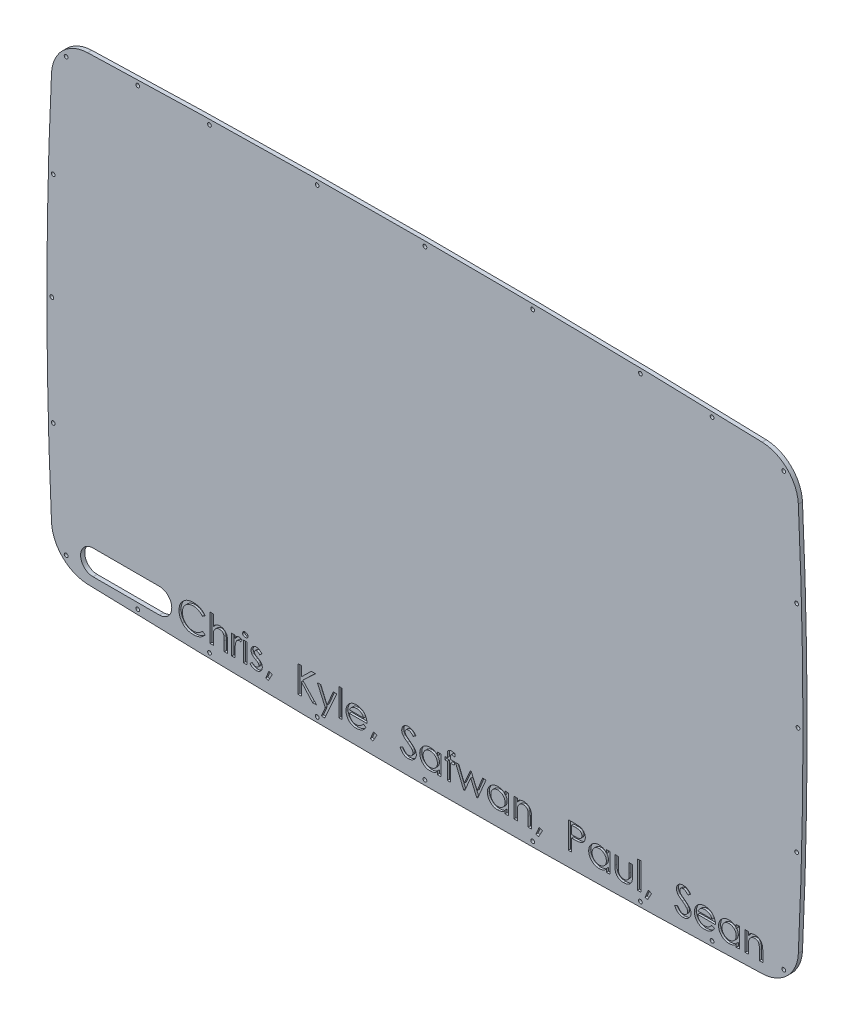
SolidWorks part; units mm, degrees
ref_plane "Front" through (0, 0, 0) normal (0, 0, 1) x (1, 0, 0)
ref_plane "Top" through (0, 0, 0) normal (0, 1, 0) x (1, 0, 0)
ref_plane "Right" through (0, 0, 0) normal (1, 0, 0) x (0, 0, -1)
sketch "Sketch1" plane through (0, 0, 0) normal (0, 0, 1) x (1, 0, 0)
  line L0 (79.622, -180.7786) -> (85.5592, -180.7149)
  line L1 (223.1034, -177.9577) -> (258.4236, -176.8528)
  circle A0 centre (-274.9542, -165.9116) radius 1.435
  arc A93 (-279.7814, -166.2105) -> (-275.1845, -170.7425) centre (-257.4604, -148.1676) ccw
  arc A94 (275.1845, -170.7425) -> (279.7814, -166.2105) centre (257.4604, -148.1676) ccw
  circle A100 centre (-274.9542, 164.9337) radius 1.4351
  circle A101 centre (-284.8103, 82.061) radius 1.4351
  circle A102 centre (-285.9024, 0) radius 1.4351
  circle A103 centre (-284.8103, -83.0389) radius 1.4351
  arc A104 (-258.4236, -176.8528) -> (-223.1034, -177.9577) centre (0, 7519.4009) ccw
  circle A105 centre (-220.0271, -174.2607) radius 1.4351
  circle A106 centre (-165.1, -175.6347) radius 1.4351
  arc A107 (-162.2131, -179.4816) -> (-85.5592, -180.7149) centre (0, 7519.4009) ccw
  arc A108 (-168.1492, -179.3542) -> (-162.2131, -179.4816) centre (0, 7519.4009) ccw
  circle A109 centre (-82.55, -176.963) radius 1.4351
  circle A110 centre (0, -177.4057) radius 1.4351
  circle A111 centre (82.55, -176.963) radius 1.4351
  circle A112 centre (165.1, -175.6347) radius 1.4351
  circle A113 centre (220.0271, -174.2607) radius 1.4351
  circle A114 centre (284.8103, -83.0389) radius 1.4351
  circle A115 centre (285.9024, 0) radius 1.4351
  circle A116 centre (284.8103, 82.061) radius 1.4351
  circle A117 centre (274.9542, 164.9337) radius 1.4351
  circle A118 centre (220.0271, 173.2828) radius 1.4351
  circle A119 centre (165.1, 174.6568) radius 1.4351
  circle A120 centre (82.55, 175.9851) radius 1.4351
  circle A121 centre (0, 176.4278) radius 1.4351
  circle A122 centre (-82.55, 175.9851) radius 1.4351
  circle A123 centre (-220.0271, 173.2828) radius 1.4351
  circle A124 centre (-165.1, 174.6568) radius 1.4351
  arc A125 (-162.2131, 178.5037) -> (-168.1492, 178.3763) centre (0, -7520.3788) ccw
  arc A126 (-85.5592, 179.737) -> (-162.2131, 178.5037) centre (0, -7520.3788) ccw
  arc A127 (-79.622, 179.8007) -> (-85.5592, 179.737) centre (0, -7520.3788) ccw
  arc A128 (-2.9688, 180.2118) -> (-79.622, 179.8007) centre (0, -7520.3788) ccw
  arc A129 (2.9688, 180.2118) -> (-2.9688, 180.2118) centre (0, -7520.3788) ccw
  arc A130 (79.622, 179.8007) -> (2.9688, 180.2118) centre (0, -7520.3788) ccw
  arc A131 (85.5592, 179.737) -> (79.622, 179.8007) centre (0, -7520.3788) ccw
  arc A132 (162.2131, 178.5037) -> (85.5592, 179.737) centre (0, -7520.3788) ccw
  arc A133 (168.1492, 178.3763) -> (162.2131, 178.5037) centre (0, -7520.3788) ccw
  arc A134 (217.1671, 177.1496) -> (168.1492, 178.3763) centre (0, -7520.3788) ccw
  arc A135 (223.1034, 176.9798) -> (217.1671, 177.1496) centre (0, -7520.3788) ccw
  arc A136 (258.4236, 175.8749) -> (223.1034, 176.9798) centre (0, -7520.3788) ccw
  arc A137 (275.1845, 169.7646) -> (258.4236, 175.8749) centre (257.4604, 147.1897) ccw
  arc A138 (279.7814, 165.2326) -> (275.1845, 169.7646) centre (257.4604, 147.1897) ccw
  arc A139 (286.1291, 148.559) -> (279.7814, 165.2326) centre (257.4604, 147.1897) ccw
  arc A140 (288.513, 85.1308) -> (286.1291, 148.559) centre (-2834.64, -0.4889) ccw
  arc A141 (288.6701, 79.1915) -> (288.513, 85.1308) centre (-2834.64, -0.4889) ccw
  arc A142 (289.6845, 2.9713) -> (288.6701, 79.1915) centre (-2834.64, -0.4889) ccw
  arc A143 (289.6854, -2.9701) -> (289.6845, 2.9713) centre (-2834.64, -0.4889) ccw
  arc A144 (288.6701, -80.1694) -> (289.6854, -2.9701) centre (-2834.64, -0.4889) ccw
  arc A145 (288.513, -86.1087) -> (288.6701, -80.1694) centre (-2834.64, -0.4889) ccw
  arc A146 (286.1291, -149.5369) -> (288.513, -86.1087) centre (-2834.64, -0.4889) ccw
  arc A147 (279.7814, -166.2105) -> (286.1291, -149.5369) centre (257.4604, -148.1676) ccw
  arc A148 (275.1845, -170.7425) -> (279.7814, -166.2105) centre (257.4604, -148.1676) ccw
  arc A149 (258.4236, -176.8528) -> (275.1845, -170.7425) centre (257.4604, -148.1676) ccw
  arc A150 (217.1671, -178.1275) -> (223.1034, -177.9577) centre (0, 7519.4009) ccw
  arc A151 (168.1492, -179.3542) -> (217.1671, -178.1275) centre (0, 7519.4009) ccw
  arc A152 (85.5592, -180.7149) -> (162.2131, -179.4816) centre (0, 7519.4009) ccw
  arc A153 (162.2131, -179.4816) -> (168.1492, -179.3542) centre (0, 7519.4009) ccw
  arc A154 (2.9688, -181.1897) -> (79.622, -180.7786) centre (0, 7519.4009) ccw
  arc A155 (-2.9688, -181.1897) -> (2.9688, -181.1897) centre (0, 7519.4009) ccw
  arc A156 (-79.622, -180.7786) -> (-2.9688, -181.1897) centre (0, 7519.4009) ccw
  arc A157 (-85.5592, -180.7149) -> (-79.622, -180.7786) centre (0, 7519.4009) ccw
  arc A158 (-217.1671, -178.1275) -> (-168.1492, -179.3542) centre (0, 7519.4009) ccw
  arc A159 (-223.1034, -177.9577) -> (-217.1671, -178.1275) centre (0, 7519.4009) ccw
  arc A160 (-275.1845, -170.7425) -> (-258.4236, -176.8528) centre (-257.4604, -148.1676) ccw
  arc A161 (-279.7814, -166.2105) -> (-275.1845, -170.7425) centre (-257.4604, -148.1676) ccw
  arc A162 (-286.1291, -149.5369) -> (-279.7814, -166.2105) centre (-257.4604, -148.1676) ccw
  arc A163 (-288.513, -86.1087) -> (-286.1291, -149.5369) centre (2834.64, -0.4889) ccw
  arc A164 (-288.6701, -80.1694) -> (-288.513, -86.1087) centre (2834.64, -0.4889) ccw
  arc A165 (-289.6854, -2.9701) -> (-288.6701, -80.1694) centre (2834.64, -0.4889) ccw
  arc A166 (-289.6845, 2.9713) -> (-289.6854, -2.9701) centre (2834.64, -0.4889) ccw
  arc A167 (-288.6701, 79.1915) -> (-289.6845, 2.9713) centre (2834.64, -0.4889) ccw
  arc A168 (-288.513, 85.1308) -> (-288.6701, 79.1915) centre (2834.64, -0.4889) ccw
  arc A169 (-286.1291, 148.559) -> (-288.513, 85.1308) centre (2834.64, -0.4889) ccw
  arc A170 (-279.7814, 165.2326) -> (-286.1291, 148.559) centre (-257.4604, 147.1897) ccw
  arc A171 (-275.1845, 169.7646) -> (-279.7814, 165.2326) centre (-257.4604, 147.1897) ccw
  arc A172 (-258.4236, 175.8749) -> (-275.1845, 169.7646) centre (-257.4604, 147.1897) ccw
  arc A173 (-223.1034, 176.9798) -> (-258.4236, 175.8749) centre (0, -7520.3788) ccw
  arc A174 (-217.1671, 177.1496) -> (-223.1034, 176.9798) centre (0, -7520.3788) ccw
  arc A175 (-168.1492, 178.3763) -> (-217.1671, 177.1496) centre (0, -7520.3788) ccw
  circle A176 centre (274.9542, -165.9116) radius 1.4351
extrude "Boss-Extrude1" add sketch "Sketch1" along normal blind 3.175
sketch "Sketch2" plane through (0, 0, 3.175) normal (0, 0, 1) x (1, 0, 0)
  line L0 (-254.3171, -160.2907) -> (-203.5171, -160.2907) construction
  line L1 (-254.3171, -150.7657) -> (-203.5171, -150.7657)
  line L2 (-254.3171, -169.8157) -> (-203.5171, -169.8157)
  arc A0 (-254.3171, -150.7657) -> (-254.3171, -169.8157) centre (-254.3171, -160.2907) ccw
  arc A1 (-203.5171, -169.8157) -> (-203.5171, -150.7657) centre (-203.5171, -160.2907) ccw
  circle A2 centre (-220.0271, -174.2607) radius 1.4351 construction
  point P2 (-228.9171, -160.2907)
  dimension "D1" = 19.05
  dimension "D2" = 50.8
  dimension "D3" = 13.97
  dimension "D4" = 8.89
extrude "Cut-Extrude1" cut sketch "Sketch2" against normal through all
sketch "Sketch3" plane through (0, 0, 3.175) normal (0, 0, 1) x (1, 0, 0)
  text T0 "<b>Chris,  Kyle,  Safwan,  Paul,  Sean</b>" font "Century Gothic" height 20.32
  point P1 (-169.4115, -159.3132)
  point P2 (-140.6479, -163.1587)
  point P3 (-183.9847, -168.8777)
  point P4 (0, 0)
  point P5 (0, 0)
  point P6 (-183.9886, -168.2834)
  point P7 (0, 0)
  point P8 (-189.9904, -169.2604)
extrude "Cut-Extrude2" cut sketch "Sketch3" against normal blind 1.5875
